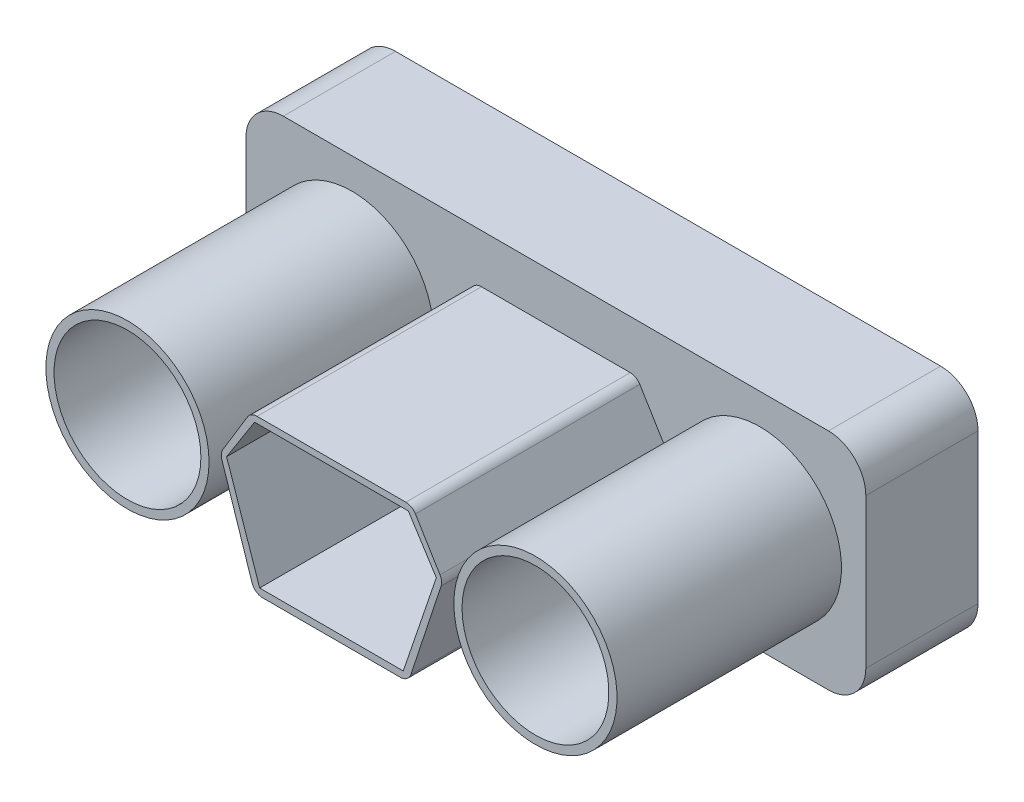
SolidWorks part; units mm, degrees
material "201 Annealed Stainless Steel (SS)"
ref_plane "Front Plane" through (0, 0, 0) normal (0, 0, 1) x (1, 0, 0)
ref_plane "Top Plane" through (0, 0, 0) normal (0, 1, 0) x (1, 0, 0)
ref_plane "Right Plane" through (0, 0, 0) normal (1, 0, 0) x (0, 0, -1)
sketch "Sketch1" plane through (0, 0, 0) normal (0, 0, 1) x (1, 0, 0)
  line L1 (-8.2871, 3) -> (8.2871, 3)
  line L2 (-8.2871, 3) -> (-8.2871, -3)
  line L3 (-8.2871, -3) -> (8.2871, -3)
  line L4 (8.2871, 3) -> (8.2871, -3)
  line L5 (-8.2871, 3) -> (8.2871, -3) construction
  line L6 (-8.2871, -3) -> (8.2871, 3) construction
  point P0 (0, 0)
extrude "Boss-Extrude1" add sketch "Sketch1" along normal blind 3
sketch "Sketch2" plane through (0, 0, 3) normal (0, 0, 1) x (1, 0, 0)
  line L0 (0, 0) -> (0, -4.01) construction
  line L1 (-2.056, -2.4298) -> (2.056, -2.4298)
  line L2 (2.056, -2.4298) -> (2.9735, 0.3568)
  line L3 (2.9735, 0.3568) -> (2.1579, 1.6991)
  line L4 (2.1579, 1.6991) -> (-2.1579, 1.6991)
  line L5 (-2.056, -2.4298) -> (-2.9735, 0.3568)
  line L6 (-2.9735, 0.3568) -> (-2.1579, 1.6991)
  line L7 (-1.92, -2.2429) -> (1.92, -2.2429)
  line L8 (1.92, -2.2429) -> (2.8036, 0.3568)
  line L9 (2.8036, 0.3568) -> (2.056, 1.5292)
  line L10 (2.056, 1.5292) -> (-2.056, 1.5292)
  line L11 (-1.92, -2.2429) -> (-2.8036, 0.3568)
  line L12 (-2.8036, 0.3568) -> (-2.056, 1.5292)
  circle A0 centre (-5.4543, 0) radius 2.1818
  circle A1 centre (5.4543, 0) radius 2.1818
  circle A2 centre (-5.4543, 0) radius 1.9635
  circle A3 centre (5.4543, 0) radius 1.9635
  point P13 (0, -2.4298)
  point P15 (0, 1.6991)
  point P21 (0, -2.2429)
  point P23 (0, 1.5292)
extrude "Boss-Extrude2" add sketch "Sketch2" along normal blind 6
fillet "Fillet2" radius 1 4 edges at (8.2871, -3, 1.5) (8.2871, 3, 1.5) (-8.2871, -3, 1.5) (-8.2871, 3, 1.5)
fillet "Fillet3" radius 0.3 6 edges at (-2.9735, 0.3568, 6) (-2.056, -2.4298, 6) (2.056, -2.4298, 6) (2.9735, 0.3568, 6) (2.1579, 1.6991, 6) (-2.1579, 1.6991, 6)
